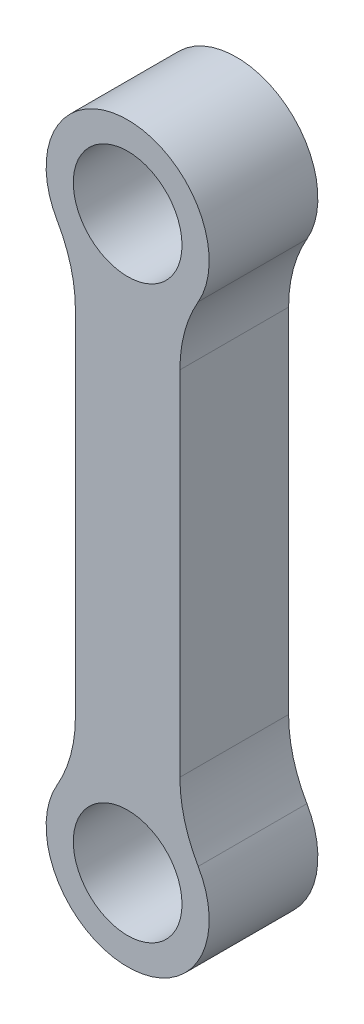
SolidWorks part; units mm, degrees
material "Gray Cast Iron"
ref_plane "Front" through (0, 0, 0) normal (0, 0, 1) x (1, 0, 0)
ref_plane "Top" through (0, 0, 0) normal (0, 1, 0) x (1, 0, 0)
ref_plane "Right" through (0, 0, 0) normal (1, 0, 0) x (0, 0, -1)
sketch "Sketch6" plane through (0, 0, 0) normal (0, 0, 1) x (1, 0, 0)
  line L0 (0, 0) -> (0, 21) construction
  circle A0 centre (0, 0) radius 3
  circle A1 centre (0, 21) radius 3
extrude "Boss-Extrude4" add sketch "Sketch6" along normal blind 4
sketch "Sketch7" plane through (0, 0, 4) normal (0, 0, 1) x (1, 0, 0)
  circle A0 centre (0, 21) radius 2
  circle A1 centre (0, 0) radius 2
extrude "Cut-Extrude3" cut sketch "Sketch7" against normal blind 4
sketch "Sketch8" plane through (0, 0, 4) normal (0, 0, 1) x (1, 0, 0)
  line L0 (0, 21) -> (0, 0) construction
  line L1 (-3.673, 19) -> (2.9442, 19) construction
  line L2 (-3.3815, 2) -> (3.3815, 2) construction
  line L4 (1.9229, 19) -> (-1.9229, 19)
  line L5 (1.9229, 19) -> (1.9229, 2)
  line L6 (1.9229, 2) -> (-1.9229, 2)
  line L7 (-1.9229, 19) -> (-1.9229, 2)
  line L8 (1.9229, 19) -> (-1.9229, 2) construction
  line L9 (1.9229, 2) -> (-1.9229, 19) construction
  point P8 (0, 10.5)
  dimension "D1" = 2
  dimension "D2" = 2
extrude "Boss-Extrude5" add sketch "Sketch8" against normal blind 4
fillet "Fillet1" radius 5 4 edges at (-1.9229, 2.3027, 2) (1.9229, 2.3027, 2) (1.9229, 18.6973, 2) (-1.9229, 18.6973, 2)
sketch "Sketch9" plane through (0, 0, 0) normal (0, 0, -1) x (-1, 0, 0)
  circle A0 centre (0, 21) radius 2
extrude "Boss-Extrude6" add sketch "Sketch9" against normal blind 0.5
sketch "Sketch10" plane through (0, 0, 0.5) normal (0, 0, 1) x (1, 0, 0)
  circle A0 centre (0, 21) radius 1.5
extrude "Cut-Extrude4" cut sketch "Sketch10" against normal blind 0.5
sketch "Sketch11" plane through (0, 0, 0) normal (0, 0, -1) x (-1, 0, 0)
  circle A0 centre (0, 0) radius 2
extrude "Boss-Extrude7" add sketch "Sketch11" against normal blind 0.5
sketch "Sketch12" plane through (0, 0, 0.5) normal (0, 0, 1) x (1, 0, 0)
  circle A0 centre (0, 0) radius 1.5
extrude "Cut-Extrude5" cut sketch "Sketch12" against normal blind 0.5
